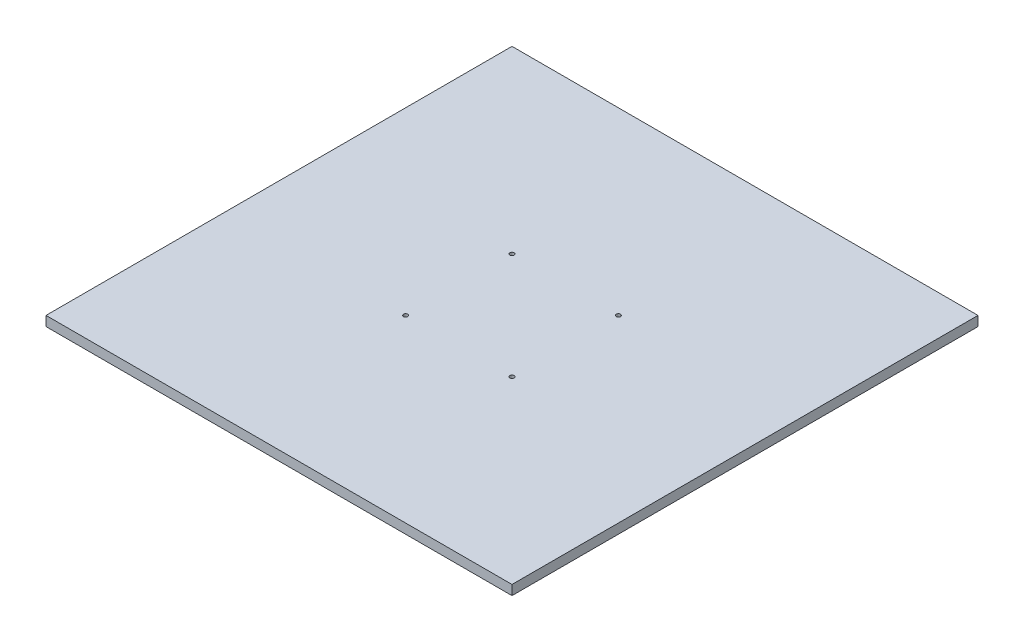
SolidWorks part; units mm, degrees
ref_plane "Front Plane" through (0, 0, 0) normal (0, 0, 1) x (1, 0, 0)
ref_plane "Top Plane" through (0, 0, 0) normal (0, 1, 0) x (1, 0, 0)
ref_plane "Right Plane" through (0, 0, 0) normal (1, 0, 0) x (0, 0, -1)
sketch "Sketch1" plane through (0, 0, 0) normal (0, 1, 0) x (1, 0, 0)
  line L1 (-69.597, -69.597) -> (69.597, -69.597) construction
  line L2 (-69.597, -69.597) -> (-69.597, 69.597) construction
  line L3 (-69.597, 69.597) -> (69.597, 69.597) construction
  line L4 (69.597, -69.597) -> (69.597, 69.597) construction
  line L5 (-69.597, -69.597) -> (69.597, 69.597) construction
  line L6 (-69.597, 69.597) -> (69.597, -69.597) construction
  line L7 (304.8, -304.8) -> (-304.8, -304.8)
  line L8 (304.8, -304.8) -> (304.8, 304.8)
  line L9 (304.8, 304.8) -> (-304.8, 304.8)
  line L10 (-304.8, -304.8) -> (-304.8, 304.8)
  line L11 (304.8, -304.8) -> (-304.8, 304.8) construction
  line L12 (304.8, 304.8) -> (-304.8, -304.8) construction
  circle A0 centre (-69.597, -69.597) radius 2.794
  circle A1 centre (69.597, -69.597) radius 2.794
  circle A2 centre (-69.597, 69.597) radius 2.794
  circle A3 centre (69.597, 69.597) radius 2.794
  point P0 (0, 0)
  point P6 (0, 0)
  dimension "D3" = 5.588
  dimension "D1" = 98.425
  dimension "D2" = 609.6
extrude "Boss-Extrude1" add sketch "Sketch1" along normal blind 12.7
